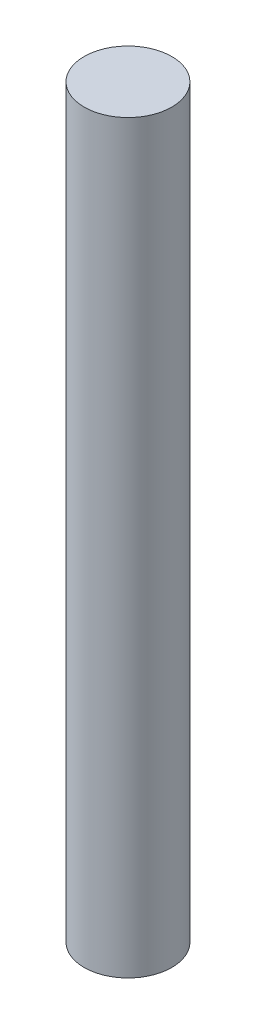
SolidWorks part; units mm, degrees
ref_plane "정면" through (0, 0, 0) normal (0, 0, 1) x (1, 0, 0)
ref_plane "윗면" through (0, 0, 0) normal (0, 1, 0) x (1, 0, 0)
ref_plane "우측면" through (0, 0, 0) normal (1, 0, 0) x (0, 0, -1)
sketch "스케치1" plane through (0, 0, 0) normal (0, 1, 0) x (1, 0, 0)
  circle A0 centre (0, 0) radius 1.5
  dimension "D1" = 3
extrude "보스-돌출1" add sketch "스케치1" along normal blind 25.5 contours A0
